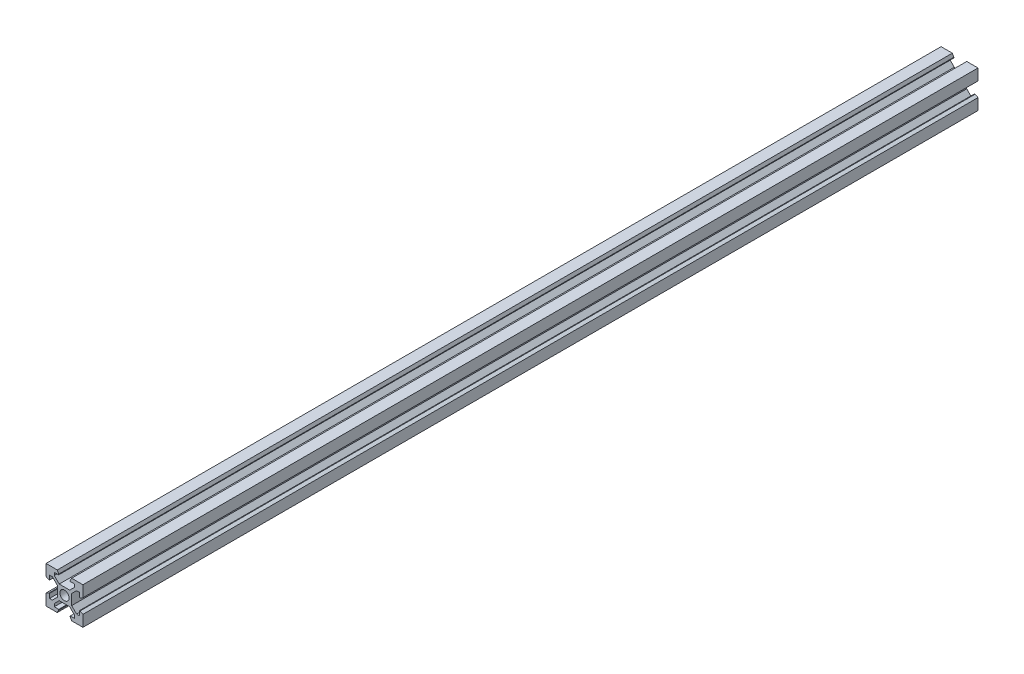
SolidWorks part; units mm, degrees
ref_plane "Front Plane" through (0, 0, 0) normal (0, 0, 1) x (1, 0, 0)
ref_plane "Top Plane" through (0, 0, 0) normal (0, 1, 0) x (1, 0, 0)
ref_plane "Right Plane" through (0, 0, 0) normal (1, 0, 0) x (0, 0, -1)
sketch "Sketch1" plane through (0, 0, 0) normal (0, 0, 1) x (1, 0, 0)
  line L0 (0, 20) -> (0, 13.8958)
  line L1 (0, 0) -> (20, 0)
  line L2 (0, 0) -> (0, 20)
  line L3 (0, 20) -> (20, 20)
  line L4 (20, 0) -> (20, 20)
  line L5 (0, 13.8958) -> (1.56, 13.1)
  line L6 (1.56, 13.1) -> (1.9, 13.1)
  line L7 (1.9, 13.1) -> (1.9, 15.5)
  line L8 (1.9, 15.5) -> (3.4393, 15.5)
  line L9 (3.4393, 15.5) -> (6.2656, 12.6737)
  line L10 (6.2656, 12.6737) -> (7.3263, 13.7344)
  line L11 (7.3263, 13.7344) -> (4.5, 16.5607)
  line L12 (4.5, 16.5607) -> (4.5, 18.1)
  line L13 (4.5, 18.1) -> (6.9, 18.1)
  line L14 (6.9, 18.1) -> (6.9, 18.44)
  line L15 (6.9, 18.44) -> (6.1, 20)
  line L16 (6.1, 20) -> (0, 20)
  line L17 (10, 10) -> (6.1, 13.9)
  line L18 (6.1, 6.1) -> (13.9, 6.1)
  line L19 (6.1, 6.1) -> (6.1, 13.9)
  line L20 (6.1, 13.9) -> (13.9, 13.9)
  line L21 (13.9, 6.1) -> (13.9, 13.9)
  line L22 (6.796, 13.204) -> (4.0494, 15.9506)
  line L23 (10, 10) -> (10, 24.9145) construction
  line L24 (13.1, 18.44) -> (13.9, 20)
  line L25 (13.1, 18.1) -> (13.1, 18.44)
  line L26 (15.5, 18.1) -> (13.1, 18.1)
  line L27 (15.5, 16.5607) -> (15.5, 18.1)
  line L28 (12.6737, 13.7344) -> (15.5, 16.5607)
  line L29 (13.7344, 12.6737) -> (12.6737, 13.7344)
  line L30 (16.5607, 15.5) -> (13.7344, 12.6737)
  line L31 (18.1, 15.5) -> (16.5607, 15.5)
  line L32 (18.1, 13.1) -> (18.1, 15.5)
  line L33 (18.44, 13.1) -> (18.1, 13.1)
  line L34 (20, 13.8958) -> (18.44, 13.1)
  line L35 (10, 10) -> (22.1718, 10)
  line L36 (20, 6.1042) -> (18.44, 6.9)
  line L37 (18.44, 6.9) -> (18.1, 6.9)
  line L38 (18.1, 6.9) -> (18.1, 4.5)
  line L39 (18.1, 4.5) -> (16.5607, 4.5)
  line L40 (16.5607, 4.5) -> (13.7344, 7.3263)
  line L41 (13.7344, 7.3263) -> (12.6737, 6.2656)
  line L42 (12.6737, 6.2656) -> (15.5, 3.4393)
  line L43 (15.5, 3.4393) -> (15.5, 1.9)
  line L44 (15.5, 1.9) -> (13.1, 1.9)
  line L45 (13.1, 1.9) -> (13.1, 1.56)
  line L46 (13.1, 1.56) -> (13.9, 0)
  line L47 (6.9, 1.56) -> (6.1, 0)
  line L48 (6.9, 1.9) -> (6.9, 1.56)
  line L49 (4.5, 1.9) -> (6.9, 1.9)
  line L50 (4.5, 3.4393) -> (4.5, 1.9)
  line L51 (7.3263, 6.2656) -> (4.5, 3.4393)
  line L52 (6.2656, 7.3263) -> (7.3263, 6.2656)
  line L53 (3.4393, 4.5) -> (6.2656, 7.3263)
  line L54 (1.9, 4.5) -> (3.4393, 4.5)
  line L55 (1.9, 6.9) -> (1.9, 4.5)
  line L56 (1.56, 6.9) -> (1.9, 6.9)
  line L57 (0, 6.1042) -> (1.56, 6.9)
  circle A0 centre (10, 10) radius 2.5
  point P21 (2.6697, 15.5)
  dimension "D3" = 5
  dimension "D1" = 20
  dimension "D2" = 20
  dimension "D4" = 10
  dimension "D5" = 10
  dimension "D6" = 7.8
  dimension "D7" = 7.8
  dimension "D8" = 6.1
  dimension "D9" = 6.1
  dimension "D10" = 6.9
  dimension "D11" = 6.9
  dimension "D12" = 6.1042
  dimension "D13" = 6.1
  dimension "D14" = 0.34
  dimension "D15" = 0.34
  dimension "D16" = 1.9
  dimension "D17" = 4.5
  dimension "D18" = 4.5
  dimension "D19" = 1.5
  dimension "D20" = 1.9
extrude "Boss-Extrude1" add sketch "Sketch1" along normal blind 485
